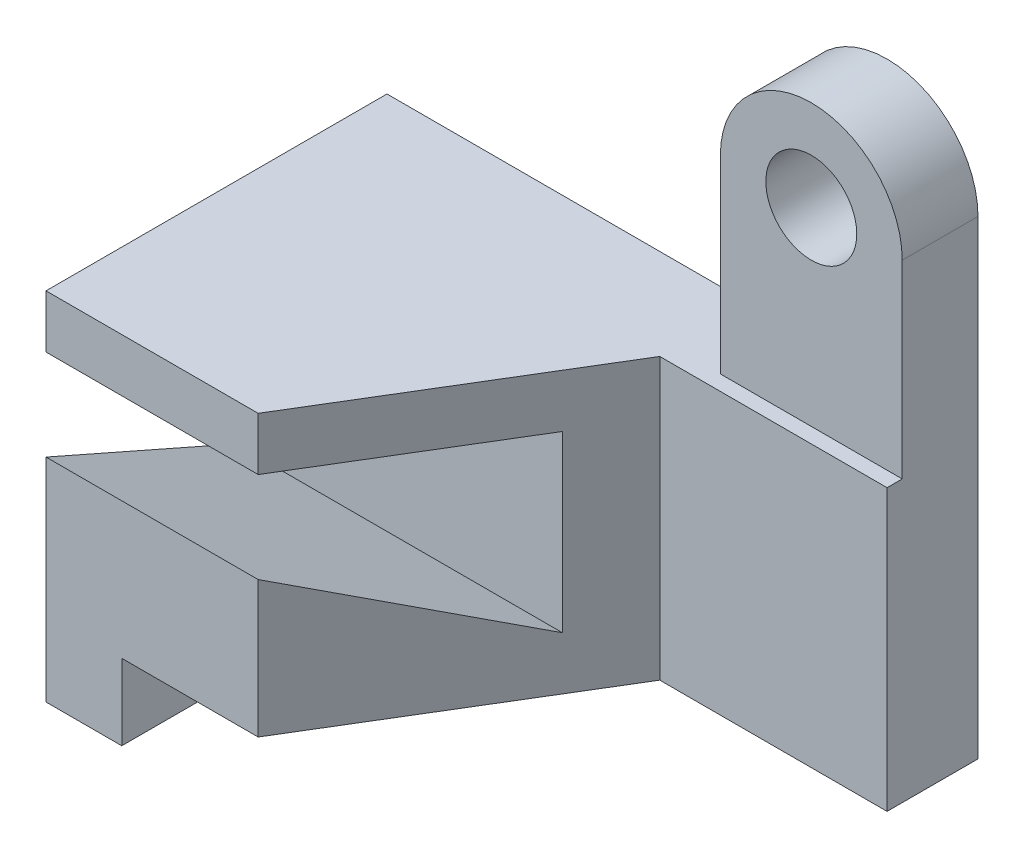
SolidWorks part; units mm, degrees
ref_plane "Front Plane" through (0, 0, 0) normal (1, 0, 0) x (0, 1, 0)
ref_plane "Top Plane" through (0, 0, 0) normal (0, 0, 1) x (0, 1, 0)
ref_plane "Right Plane" through (0, 0, 0) normal (0, 1, 0) x (-1, 0, 0)
sketch "Sketch1" plane through (0, 0, 0) normal (0, 1, 0) x (-1, 0, 0)
  line L0 (0, 0) -> (0, 21407.2957) construction
  line L1 (0, 0) -> (21407.2957, 0) construction
  line L2 (0, 0) -> (78, 0)
  line L3 (78, 0) -> (78, 45)
  line L4 (78, 45) -> (50, 45)
  line L5 (50, 45) -> (30, 12)
  line L6 (30, 12) -> (0, 12)
  line L7 (0, 12) -> (0, 0)
  dimension "D1" = 78
  dimension "D2" = 45
  dimension "D3" = 30
  dimension "D4" = 28
  dimension "D5" = 12
extrude "Boss-Extrude1" add sketch "Sketch1" along normal mid plane 37
sketch "Sketch2" plane through (-78, 0, 0) normal (-1, 0, 0) x (0, -1, 0)
  line L0 (-18.5, 45) -> (-11.5, 45)
  line L1 (-18.5, 45) -> (18.5, 45) construction
  line L2 (-11.5, 45) -> (-11.5, 20)
  line L3 (-11.5, 20) -> (11.5, 20)
  line L4 (11.5, 20) -> (0.5, 45)
  line L5 (0.5, 45) -> (18.5, 45)
  line L6 (18.5, 45) -> (18.5, 0)
  line L7 (18.5, 0) -> (-18.5, 0)
  line L8 (-18.5, 0) -> (-18.5, 45)
  line L9 (-11.5, 45) -> (0.5, 45)
  dimension "D1" = 7
  dimension "D2" = 12
  dimension "D3" = 23
  dimension "D4" = 25
extrude "Cut-Extrude1" cut sketch "Sketch2" against normal through all contours L2 L3 L4
sketch "Sketch3" plane through (0, 18.5, 0) normal (0, 1, 0) x (-1, 0, 0)
  line L0 (0, 0) -> (24, 0)
  line L1 (0, 0) -> (78, 0) construction
  line L2 (24, 0) -> (24, 10)
  line L3 (24, 10) -> (0, 10)
  line L4 (0, 12) -> (0, 0) construction
  line L5 (0, 10) -> (0, 0)
extrude "Boss-Extrude2" add sketch "Sketch3" along normal blind 25
sketch "Sketch4" plane through (0, 0, 10) normal (0, 0, 1) x (1, 0, 0)
  line L0 (-24, 43.5) -> (0, 43.5) construction
  circle A0 centre (-12, 43.5) radius 12
  circle A1 centre (-12, 43.5) radius 6
  dimension "D1" = 24
  dimension "D2" = 12
extrude "Boss-Extrude4" add sketch "Sketch4" against normal blind 10
sketch "Sketch5" plane through (0, 0, 10) normal (0, 0, 1) x (1, 0, 0)
  line L0 (-18, 43.5) -> (-6, 43.5) construction
  circle A0 centre (-12, 43.5) radius 6
extrude "Cut-Extrude2" cut sketch "Sketch5" against normal through all
sketch "Sketch6" plane through (0, 0, 45) normal (0, 0, 1) x (1, 0, 0)
  line L1 (-78, -18.5) -> (-68, -18.5)
  line L2 (-78, -18.5) -> (-78, -28.5)
  line L3 (-78, -28.5) -> (-68, -28.5)
  line L4 (-68, -18.5) -> (-68, -28.5)
  dimension "D1" = 10
  dimension "D2" = 10
extrude "Boss-Extrude5" add sketch "Sketch6" against normal blind 45
